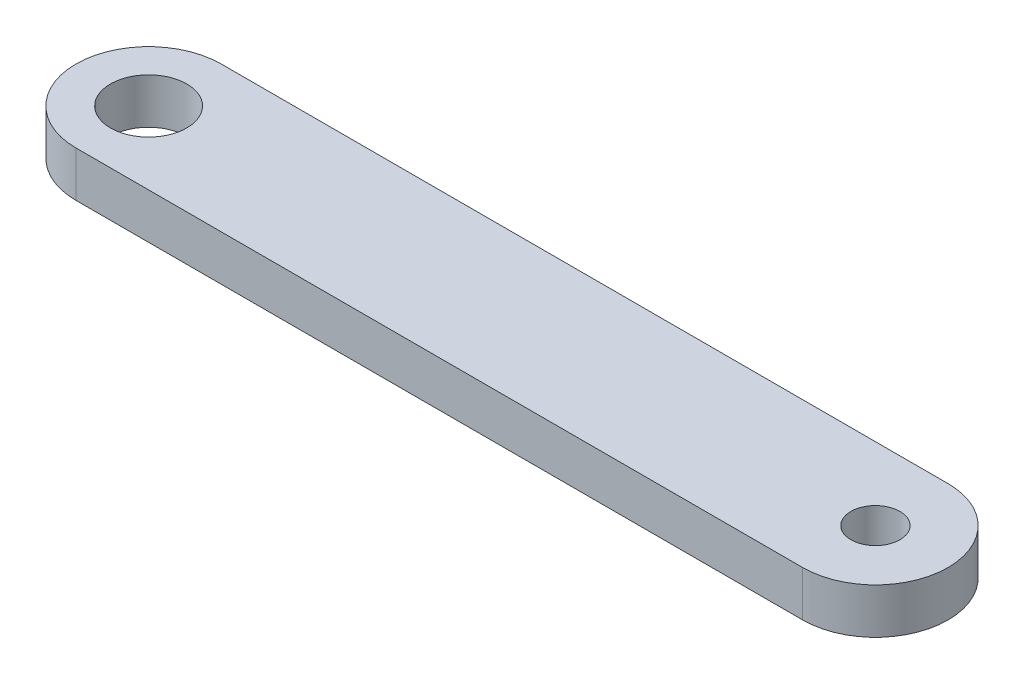
SolidWorks part; units mm, degrees
ref_plane "Front Plane" through (0, 0, 0) normal (0, 0, 1) x (1, 0, 0)
ref_plane "Top Plane" through (0, 0, 0) normal (0, 1, 0) x (1, 0, 0)
ref_plane "Right Plane" through (0, 0, 0) normal (1, 0, 0) x (0, 0, -1)
sketch "Sketch1" plane through (0, 0, 0) normal (0, 1, 0) x (1, 0, 0)
  line L0 (0, 0) -> (50.8, 0) construction
  line L1 (0, 5.08) -> (50.8, 5.08)
  line L2 (0, -5.08) -> (50.8, -5.08)
  arc A0 (0, 5.08) -> (0, -5.08) centre (0, 0) ccw
  arc A1 (50.8, -5.08) -> (50.8, 5.08) centre (50.8, 0) ccw
  circle A2 centre (0, 0) radius 2.667
  circle A3 centre (50.8, 0) radius 1.7145
  point P3 (25.4, 0)
  dimension "D3" = 5.334
  dimension "D4" = 3.429
  dimension "D1" = 10.16
  dimension "D2" = 50.8
extrude "Boss-Extrude1" add sketch "Sketch1" along normal mid plane 3.175
